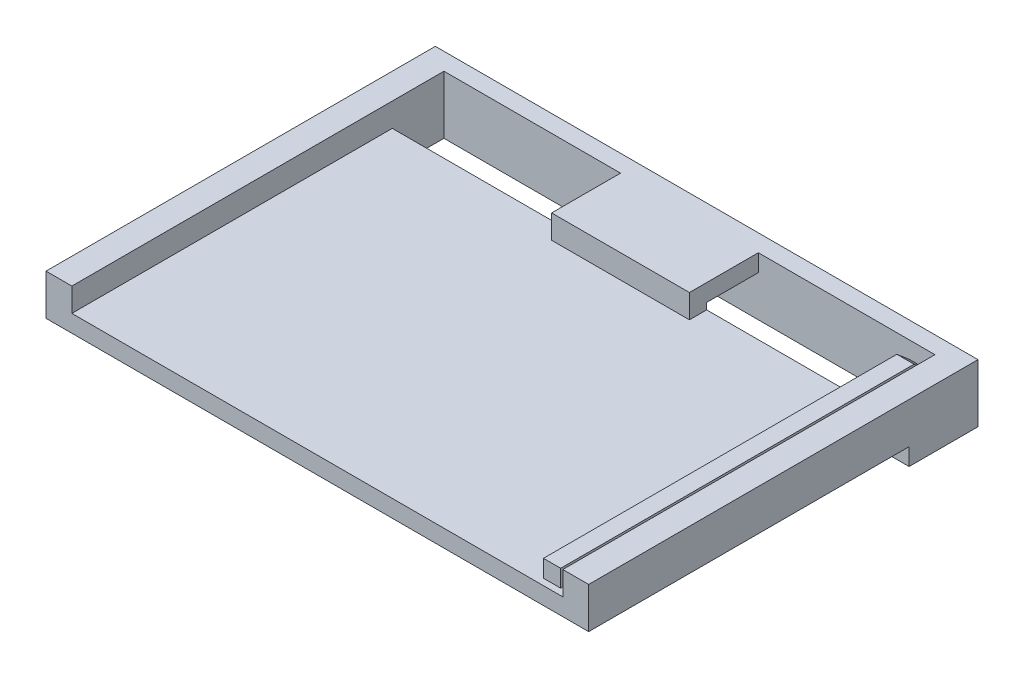
SolidWorks part; units mm, degrees
ref_plane "Front Plane" through (0, 0, 0) normal (0, 0, 1) x (1, 0, 0)
ref_plane "Top Plane" through (0, 0, 0) normal (0, 1, 0) x (1, 0, 0)
ref_plane "Right Plane" through (0, 0, 0) normal (1, 0, 0) x (0, 0, -1)
sketch "Sketch1" plane through (0, 0, 0) normal (0, 1, 0) x (1, 0, 0)
  line L0 (0, 0) -> (0, 22.6) construction
  line L1 (-31.5, 22.6) -> (31.5, 22.6)
  line L2 (-31.5, 22.6) -> (-31.5, -22.6)
  line L3 (-31.5, -22.6) -> (31.5, -22.6)
  line L4 (31.5, 22.6) -> (31.5, -22.6)
  line L5 (0, 0) -> (-31.5, 0) construction
  dimension "D1" = 63
  dimension "D2" = 45.2
extrude "Boss-Extrude1" add sketch "Sketch1" along normal blind 6.75
sketch "Sketch2" plane through (0, 0, 0) normal (0, -1, 0) x (1, 0, 0)
  line L0 (31.5, 22.6) -> (31.5, -22.6) construction
  line L1 (31.5, -14.6) -> (-31.5, -14.6)
  line L2 (31.5, -14.6) -> (31.5, 22.6)
  line L3 (31.5, 22.6) -> (-31.5, 22.6)
  line L4 (-31.5, -14.6) -> (-31.5, 22.6)
  line L5 (31.5, -22.6) -> (-31.5, -22.6) construction
  dimension "D1" = 8
extrude "Cut-Extrude1" cut sketch "Sketch2" against normal blind 2
sketch "Sketch3" plane through (0, 6.75, 0) normal (0, 1, 0) x (1, 0, 0)
  line L0 (-31.5, -22.6) -> (31.5, -22.6) construction
  line L1 (-28.5, 20.6) -> (-8, 20.6)
  line L2 (-28.5, 20.6) -> (-28.5, -22.6)
  line L3 (-28.5, -22.6) -> (28.5, -22.6)
  line L4 (28.5, 20.6) -> (28.5, -22.6)
  line L5 (-31.5, 22.6) -> (-31.5, -22.6) construction
  line L6 (31.5, 22.6) -> (-31.5, 22.6) construction
  line L7 (31.5, -22.6) -> (31.5, 22.6) construction
  line L8 (0, 0) -> (0, 38.2416) construction
  line L9 (8, 20.6) -> (28.5, 20.6)
  line L11 (-8, 20.6) -> (-8, 12.6)
  line L12 (-8, 12.6) -> (8, 12.6)
  line L13 (8, 20.6) -> (8, 12.6)
  dimension "D1" = 3
  dimension "D2" = 2
  dimension "D3" = 3
  dimension "D4" = 16
  dimension "D5" = 10
extrude "Cut-Extrude2" cut sketch "Sketch3" against normal offset from surface (2.75 mm away) 2 up to face at (0, 2, 4)
sketch "Sketch4" plane through (0, 0, 0) normal (0, -1, 0) x (1, 0, 0)
  line L0 (-31.5, -14.6) -> (31.5, -14.6) construction
  line L1 (-28.5, -20.6) -> (-8, -20.6)
  line L2 (-28.5, -20.6) -> (-28.5, -14.6)
  line L3 (-28.5, -14.6) -> (-8, -14.6)
  line L4 (-8, -20.6) -> (-8, -14.6)
  line L5 (-8, -12.6) -> (-8, -20.6) construction
  line L6 (28.5, 22.6) -> (28.5, -20.6) construction
  line L7 (8, -20.6) -> (28.5, -20.6)
  line L8 (8, -20.6) -> (8, -14.6)
  line L9 (8, -14.6) -> (28.5, -14.6)
  line L10 (28.5, -20.6) -> (28.5, -14.6)
extrude "Cut-Extrude3" cut sketch "Sketch4" against normal through all
sketch "Sketch5" plane through (0, 0, 0) normal (0, -1, 0) x (1, 0, 0)
  line L1 (8, -20.6) -> (-8, -20.6)
  line L2 (8, -20.6) -> (8, -14.6)
  line L3 (8, -14.6) -> (-8, -14.6)
  line L4 (-8, -20.6) -> (-8, -14.6)
extrude "Cut-Extrude4" cut sketch "Sketch5" against normal offset from surface (4.75 mm away) 2 up to face at (0, 6.75, -5.2)
sketch "Sketch6" plane through (28.5, 0, 0) normal (-1, 0, 0) x (0, 0, 1)
  line L0 (-20.3511, 4.75) -> (-20.6, 0)
  line L1 (-19.2261, 4.75) -> (-19.2261, -2.093) construction
  line L2 (22.6, 6.75) -> (-20.6, 6.75) construction
  line L3 (-18.1011, 4.75) -> (-17.8521, 0)
  line L4 (-22.6, 0) -> (-14.6, 0) construction
  line L5 (-20.6, 0) -> (-17.8521, 0)
  arc A0 (-18.1011, 4.75) -> (-20.3511, 4.75) centre (-19.2261, 4.75) ccw
  dimension "D2" = 2.25
  dimension "D1" = 3
  dimension "D3" = 2
extrude "Cut-Extrude5" cut sketch "Sketch6" against normal blind 1
sketch "Sketch7" plane through (29.5, 0, 0) normal (-1, 0, 0) x (0, 0, 1)
  circle A0 centre (-19.2261, 4.75) radius 1
  arc A1 (-18.1011, 4.75) -> (-20.3511, 4.75) centre (-19.2261, 4.75) ccw construction
  dimension "D1" = 0.125
extrude "Boss-Extrude2" add sketch "Sketch7" along normal blind 0.75 from offset 0.5 separate body
sketch "Sketch8" plane through (28.25, 0, 0) normal (-1, 0, 0) x (0, 0, 1)
  line L0 (-19.8767, 5.5094) -> (-18.4288, 6.75)
  line L1 (-20.2261, 4.75) -> (-21.0425, 9.1165) construction
  line L2 (22.6, 6.75) -> (-20.6, 6.75) construction
  line L3 (22.6, 6.75) -> (-18.4288, 6.75)
  line L4 (-18.5754, 3.9906) -> (-17.6891, 4.75)
  line L5 (-17.6891, 4.75) -> (22.6, 4.75)
  line L6 (22.6, 4.75) -> (22.6, 6.75)
  circle A1 centre (-19.2261, 4.75) radius 1 construction
  arc A2 (-19.8767, 5.5094) -> (-18.5754, 3.9906) centre (-19.2261, 4.75) ccw
  dimension "D1" = 60
  dimension "D2" = 2
extrude "Boss-Extrude3" add sketch "Sketch8" along normal blind 2
sketch "Sketch9" plane through (0, 4, 0) normal (0, 1, 0) x (1, 0, 0)
  line L0 (28.5, -22.6) -> (28.5, 14.6) construction
  line L1 (-28.5, 14.6) -> (28.5, 14.6) construction
  line L5 (8, 20.6) -> (28.5, 20.6)
  line L6 (8, 20.6) -> (8, 14.6)
  line L7 (24.5, 12.6) -> (28.5, 12.6)
  line L8 (28.5, 20.6) -> (28.5, 12.6)
  line L9 (8, 12.6) -> (-8, 12.6) construction
  line L10 (24.5, 12.6) -> (24.5, 14.6)
  line L13 (8, 14.6) -> (24.5, 14.6)
  dimension "D1" = 4
extrude "Cut-Extrude6" cut sketch "Sketch9" against normal through all
other "Save Bodies1"
